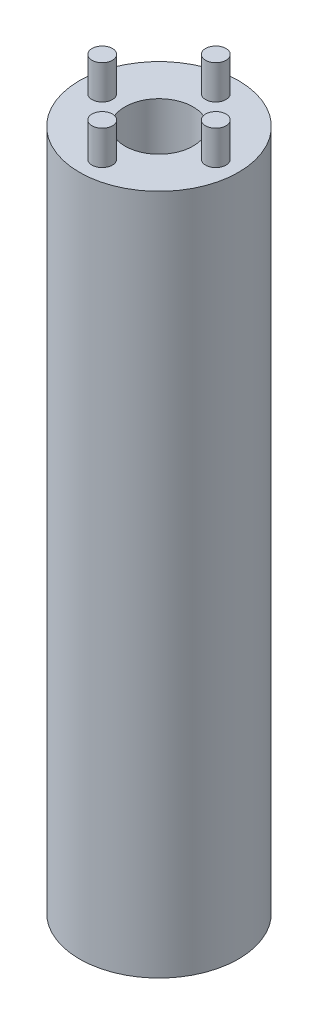
SolidWorks part; units mm, degrees
ref_plane "前视基准面" through (0, 0, 0) normal (0, 0, 1) x (1, 0, 0)
ref_plane "上视基准面" through (0, 0, 0) normal (0, 1, 0) x (1, 0, 0)
ref_plane "右视基准面" through (0, 0, 0) normal (1, 0, 0) x (0, 0, -1)
other "Configuration Table"
sketch "草图1" plane through (0, 0, 0) normal (0, 1, 0) x (1, 0, 0)
  circle A0 centre (0, 0) radius 1.5
  circle A1 centre (0, 0) radius 3.5
  circle A2 centre (0, 0) radius 2.5
  circle A3 centre (0, 2.5) radius 0.45
  dimension "D1" = 3
  dimension "D2" = 7
  dimension "D3" = 5
  dimension "D4" = 0.9
extrude "凸台-拉伸2" add sketch "草图1" along normal blind 30 contours A1 A3 A2 | A3 A2 A0 | A2 A3 | A2 A3
sketch "草图3" plane through (0, 30, 0) normal (0, 1, 0) x (1, 0, 0)
  circle A0 centre (0, 0) radius 2.5
  circle A1 centre (0, 2.5) radius 0.45
  circle A2 centre (2.5, 0) radius 0.45
  circle A3 centre (0, -2.5) radius 0.45
  circle A4 centre (-2.5, 0) radius 0.45
  dimension "D1" = 5
  dimension "D2" = 0.9
  dimension "D3" = 4
extrude "凸台-拉伸4" add sketch "草图3" along normal blind 1.5 contours A0 A4 | A0 A4 | A0 A1 | A0 A1 | A0 A2 | A0 A2 | A0 A3 | A0 A3
